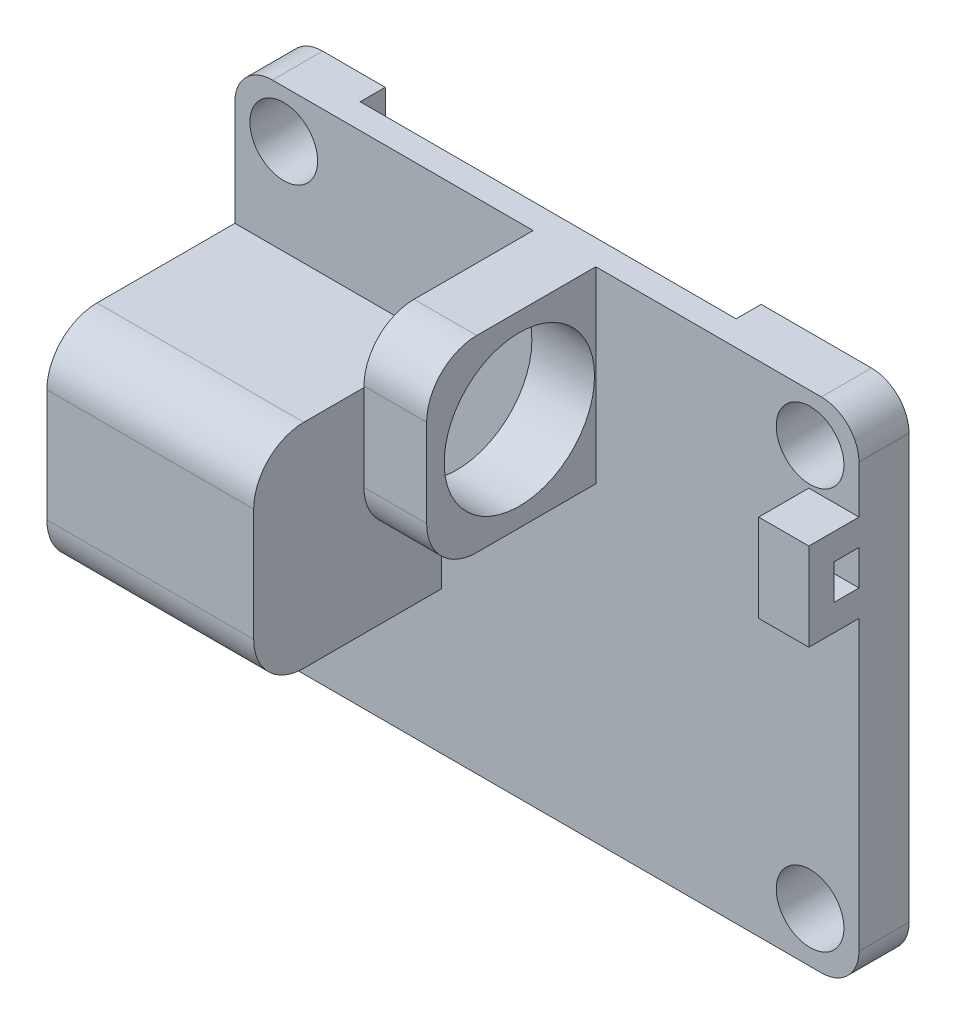
SolidWorks part; units mm, degrees
ref_plane "Alzado" through (0, 0, 0) normal (0, 0, 1) x (1, 0, 0)
ref_plane "Planta" through (0, 0, 0) normal (0, 1, 0) x (1, 0, 0)
ref_plane "Vista lateral" through (0, 0, 0) normal (1, 0, 0) x (0, 0, -1)
sketch "Croquis1" plane through (0, 0, 0) normal (0, 0, 1) x (1, 0, 0)
  line L1 (-56.8634, 16.1421) -> (-7.0634, 16.1421)
  line L2 (-56.8634, 16.1421) -> (-56.8634, -23.6579)
  line L3 (-56.8634, -23.6579) -> (-7.0634, -23.6579)
  line L4 (-7.0634, 16.1421) -> (-7.0634, -23.6579)
  circle A0 centre (-52.9634, 12.3421) radius 2.7
  circle A1 centre (-10.9634, 12.3421) radius 2.7
  circle A2 centre (-10.9634, -19.6579) radius 2.7
  circle A3 centre (-52.9634, -19.6579) radius 2.7
  dimension "D3" = 3.8
  dimension "D7" = 5.4
  dimension "D1" = 49.8
  dimension "D2" = 39.8
  dimension "D4" = 3.9
  dimension "D5" = 2
  dimension "D6" = 2
extrude "Saliente-Extruir1" add sketch "Croquis1" along normal blind 6
sketch "Croquis2" plane through (0, 0, 6) normal (0, 0, 1) x (1, 0, 0)
  line L0 (-56.8634, -23.6579) -> (-7.0634, 16.1421) construction
  line L2 (-49.9634, -16.7579) -> (-13.9634, -16.7579)
  line L3 (-51.9634, -14.7579) -> (-51.9634, 7.2421)
  line L4 (-49.9634, 9.2421) -> (-13.9634, 9.2421)
  line L5 (-11.9634, -14.7579) -> (-11.9634, 7.2421)
  line L6 (-51.9634, -16.7579) -> (-11.9634, 9.2421) construction
  line L7 (-51.9634, 9.2421) -> (-11.9634, -16.7579) construction
  arc A0 (-11.9634, 7.2421) -> (-13.9634, 9.2421) centre (-13.9634, 7.2421) ccw
  arc A1 (-11.9634, -14.7579) -> (-13.9634, -16.7579) centre (-13.9634, -14.7579) cw
  arc A2 (-49.9634, -16.7579) -> (-51.9634, -14.7579) centre (-49.9634, -14.7579) cw
  arc A3 (-49.9634, 9.2421) -> (-51.9634, 7.2421) centre (-49.9634, 7.2421) ccw
  point P4 (-31.9634, -3.7579)
  dimension "D3" = 2
  dimension "D1" = 40
  dimension "D2" = 26
extrude "Cortar-Extruir1" cut sketch "Croquis2" against normal blind 4
sketch "Croquis4" plane through (0, 0, 0) normal (0, 0, -1) x (-1, 0, 0)
  line L1 (56.8634, 16.1421) -> (56.8634, -23.6579) construction
  line L2 (56.8634, 4.2421) -> (61.8634, 4.2421)
  line L4 (61.8634, -11.7579) -> (56.8634, -11.7579)
  line L6 (56.8634, 4.2421) -> (61.8634, -11.7579) construction
  line L7 (57.8634, -0.2579) -> (61.8634, -0.2579)
  line L8 (57.8634, -7.2579) -> (61.8634, -7.2579)
  line L9 (61.8634, 4.2421) -> (61.8634, -0.2579)
  line L10 (61.8634, -7.2579) -> (61.8634, -11.7579)
  line L11 (56.8634, 4.2421) -> (56.8634, -0.4038)
  line L12 (56.8634, -7.112) -> (56.8634, -11.7579)
  arc A2 (57.8634, -0.2579) -> (56.8634, -0.4038) centre (57.8634, -3.7579) ccw
  arc A3 (57.8634, -7.2579) -> (56.8634, -7.112) centre (57.8634, -3.7579) cw
  dimension "D1" = 5
  dimension "D2" = 3.5
  dimension "D3" = 5
extrude "Saliente-Extruir3" add sketch "Croquis4" against normal blind 3
sketch "Croquis5" plane through (0, 0, 3) normal (0, 0, 1) x (1, 0, 0)
  circle A1 centre (-57.8634, -3.7579) radius 6.35
extrude "Cortar-Extruir2" cut sketch "Croquis5" along normal up to vertex (3 mm away)
sketch "Croquis6" plane through (0, 0, 3) normal (0, 0, 1) x (1, 0, 0)
  line L6 (-61.8634, 4.2421) -> (-51.9634, 4.2421)
  line L8 (-51.9634, -11.7579) -> (-61.8634, -11.7579)
  line L9 (-61.8634, 4.2421) -> (-61.8634, 1.1739)
  line L10 (-61.8634, -0.2579) -> (-61.8634, 4.2421) construction
  line L11 (-61.8634, -11.7579) -> (-61.8634, -8.6897)
  line L12 (-51.9634, 4.2421) -> (-48.9634, 4.2421)
  line L13 (-48.9634, 4.2421) -> (-48.9634, -11.7579)
  line L14 (-48.9634, -11.7579) -> (-51.9634, -11.7579)
  arc A5 (-61.8634, 1.1739) -> (-61.8634, -8.6897) centre (-57.8634, -3.7579) cw
extrude "Saliente-Extruir4" add sketch "Croquis6" along normal blind 10
sketch "Croquis7" plane through (0, 0, 2) normal (0, 0, 1) x (1, 0, 0)
  line L0 (-51.9634, -3.7579) -> (-51.9634, 4.2421)
  line L1 (-51.9634, 7.2421) -> (-51.9634, -14.7579) construction
  line L2 (-51.9634, 4.2421) -> (-48.9634, 4.2421)
  line L3 (-48.9634, 4.2421) -> (-48.9634, -11.7579)
  line L4 (-48.9634, -11.7579) -> (-51.9634, -11.7579)
  line L5 (-51.9634, -11.7579) -> (-51.9634, -3.7579)
extrude "Saliente-Extruir5" add sketch "Croquis7" along normal blind 2
sketch "Croquis8" plane through (0, 0, 3) normal (0, 0, 1) x (1, 0, 0)
  line L0 (-56.8634, -0.4038) -> (-56.8634, -7.112)
  arc A0 (-56.8634, -0.4038) -> (-56.8634, -7.112) centre (-56.8634, -3.7579) cw
extrude "Cortar-Extruir3" cut sketch "Croquis8" against normal up to vertex
sketch "Croquis9" plane through (0, 0, 6) normal (0, 0, 1) x (1, 0, 0)
  line L0 (-56.8634, -11.7579) -> (-56.8634, -27.4922)
  line L1 (-56.8634, -27.4922) -> (-1.8171, -27.4922)
  line L2 (-1.8171, -27.4922) -> (-1.8171, 22.8618)
  line L3 (-1.8171, 22.8618) -> (-56.8634, 22.8618)
  line L4 (-56.8634, 22.8618) -> (-56.8634, 4.2421)
  line L5 (-56.8634, 4.2421) -> (-47.1727, 4.2421)
  line L6 (-47.1727, 4.2421) -> (-47.1727, -11.7579)
  line L7 (-47.1727, -11.7579) -> (-56.8634, -11.7579)
extrude "Cortar-Extruir4" cut sketch "Croquis9" against normal blind 4
sketch "Croquis10" plane through (0, 0, 2) normal (0, 0, 1) x (1, 0, 0)
  line L0 (-7.0634, -23.6579) -> (-7.0634, 16.1421) construction
  line L1 (-7.0634, 9.3421) -> (-11.0634, 9.3421)
  line L2 (-7.0634, 9.3421) -> (-7.0634, 2.3421)
  line L3 (-7.0634, 2.3421) -> (-11.0634, 2.3421)
  line L4 (-11.0634, 9.3421) -> (-11.0634, 2.3421)
  circle A0 centre (-10.9634, 12.3421) radius 2.7 construction
  point P6 (-9.0634, 9.3421)
  dimension "D1" = 7
  dimension "D2" = 3
  dimension "D3" = 4
extrude "Saliente-Extruir6" add sketch "Croquis10" along normal blind 4
sketch "Croquis11" plane through (-7.0634, 0, 0) normal (1, 0, 0) x (0, 0, -1)
  line L0 (-6, 5.8421) -> (-2, 5.8421) construction
  line L1 (-6, 2.3421) -> (-6, 9.3421) construction
  line L2 (-2, 5.8421) -> (-2, 7.2421)
  line L3 (-2, 7.2421) -> (-4, 7.2421)
  line L4 (-4, 7.2421) -> (-4, 4.4421)
  line L5 (-4, 4.4421) -> (-2, 4.4421)
  line L6 (-2, 4.4421) -> (-2, 5.8421)
  dimension "D1" = 1.4
  dimension "D2" = 1.4
extrude "Cortar-Extruir5" cut sketch "Croquis11" against normal up to vertex
ref_plane "Plano2" through (-48.9634, 4.2421, 13) normal (0, 1, 0) x (1, 0, 0)
sketch "Croquis16" plane through (0, 0, 2) normal (0, 0, 1) x (1, 0, 0)
  line L1 (-64.1981, 16.945) -> (-35.2393, 16.945)
  line L2 (-64.1981, 16.945) -> (-64.1981, -30.9257)
  line L3 (-64.1981, -30.9257) -> (-35.2393, -30.9257)
  line L4 (-35.2393, 16.945) -> (-35.2393, -30.9257)
extrude "Cortar-Extruir6" cut sketch "Croquis16" along normal up to vertex (2 mm away)
sketch "Croquis17" plane through (0, 0, 2) normal (0, 0, 1) x (1, 0, 0)
  line L1 (-61.8634, 4.2421) -> (-56.8634, 4.2421)
  line L2 (-61.8634, 4.2421) -> (-61.8634, -11.7579)
  line L3 (-61.8634, -11.7579) -> (-56.8634, -11.7579)
  line L4 (-56.8634, 4.2421) -> (-56.8634, -11.7579)
extrude "Cortar-Extruir7" cut sketch "Croquis17" against normal blind 10
sketch "Croquis18" plane through (0, 0, 2) normal (0, 0, 1) x (1, 0, 0)
  line L0 (-56.8634, -0.4038) -> (-50.5134, -0.4038)
  line L1 (-56.8634, -7.112) -> (-50.5134, -7.112)
  line L2 (-56.8634, -0.4038) -> (-56.8634, -7.112)
  arc A0 (-50.5134, -0.4038) -> (-50.5134, -7.112) centre (-50.5134, -3.7579) cw
extrude "Cortar-Extruir8" cut sketch "Croquis18" against normal up to vertex (2 mm away)
sketch "Croquis19" plane through (0, 0, 2) normal (0, 0, 1) x (1, 0, 0)
  line L0 (-55.9053, -0.4038) -> (-56.8634, -0.4038)
  line L1 (-50.5134, -0.4038) -> (-56.8634, -0.4038) construction
  line L2 (-56.8634, -0.4038) -> (-56.8634, 2.5962)
  line L3 (-56.8634, 16.1421) -> (-56.8634, -0.4038) construction
  line L4 (-55.9053, -7.112) -> (-56.8634, -7.112)
  line L5 (-56.8634, -7.112) -> (-50.5134, -7.112) construction
  line L6 (-56.8634, -7.112) -> (-56.8634, -10.112)
  line L7 (-56.8634, -7.112) -> (-56.8634, -23.6579) construction
  circle A0 centre (-50.5134, -3.7579) radius 6.35
  arc A1 (-56.8634, 2.5962) -> (-56.8634, -10.112) centre (-50.5093, -3.7579) cw
  dimension "D1" = 3
sketch "Croquis20" plane through (0, 0, 2) normal (0, 0, 1) x (1, 0, 0)
  line L0 (-56.8634, -0.4038) -> (-56.8634, -7.112)
  line L1 (-56.8634, -7.112) -> (-50.5134, -7.112)
  line L2 (-56.8634, -0.4038) -> (-50.5134, -0.4038)
  arc A0 (-50.5134, -0.4038) -> (-50.5134, -7.112) centre (-50.5134, -3.7579) cw
extrude "Saliente-Extruir7" add sketch "Croquis20" against normal up to vertex (2 mm away)
sketch "Croquis22" plane through (-56.8634, 0, 0) normal (-1, 0, 0) x (0, 0, 1)
  line L0 (2, -3.7579) -> (2, 4.7421)
  line L1 (2, 16.1421) -> (2, -23.6579) construction
  line L2 (2, 4.7421) -> (13, 4.7421)
  line L3 (17, 0.7421) -> (17, -8.2579)
  line L4 (13, -12.2579) -> (2, -12.2579)
  line L5 (2, -12.2579) -> (2, -3.7579)
  line L6 (2, -3.7579) -> (8.55, -3.7579) construction
  arc A1 (17, -8.2579) -> (13, -12.2579) centre (13, -8.2579) cw
  arc A2 (13, 4.7421) -> (17, 0.7421) centre (13, 0.7421) cw
  circle A3 centre (8.55, -3.7579) radius 6.5
  dimension "D1" = 4
  dimension "D2" = 6.55
extrude "Saliente-Extruir9" add sketch "Croquis22" against normal blind 15
sketch "Croquis23" plane through (-41.8634, 0, 0) normal (1, 0, 0) x (0, 0, -1)
  line L0 (-13, -12.2579) -> (-2, -12.2579)
  line L1 (-2, -12.2579) -> (-2, 4.7421)
  line L2 (-2, 4.7421) -> (-13, 4.7421)
  line L3 (-17, 0.7421) -> (-17, -8.2579)
  arc A0 (-13, -12.2579) -> (-17, -8.2579) centre (-13, -8.2579) cw
  arc A1 (-17, 0.7421) -> (-13, 4.7421) centre (-13, 0.7421) cw
extrude "Saliente-Extruir10" add sketch "Croquis23" along normal blind 1.5
sketch "Croquis25" plane through (0, 0, 2) normal (0, 0, 1) x (1, 0, 0)
  line L1 (-33.0634, 16.1421) -> (-28.0634, 16.1421)
  line L2 (-33.0634, 16.1421) -> (-33.0634, 1.1421)
  line L3 (-33.0634, 1.1421) -> (-28.0634, 1.1421)
  line L4 (-28.0634, 16.1421) -> (-28.0634, 1.1421)
  line L6 (-7.0634, -23.6579) -> (-7.0634, 2.3421) construction
  dimension "D1" = 15
  dimension "D2" = 5
  dimension "D3" = 21
extrude "Saliente-Extruir11" add sketch "Croquis25" along normal blind 13.5
sketch "Croquis26" plane through (-28.0634, 0, 0) normal (1, 0, 0) x (0, 0, -1)
  line L0 (-2, 8.6421) -> (-8.1, 8.6421) construction
  line L1 (-2, 1.1421) -> (-2, 16.1421) construction
  circle A0 centre (-8.1, 8.6421) radius 6
extrude "Cortar-Extruir9" cut sketch "Croquis26" against normal up to vertex
fillet "Redondeo2" radius 4 2 edges at (-30.5634, 1.1421, 15.5) (-30.5634, 16.1421, 15.5)
sketch "Croquis27" plane through (0, 0, 0) normal (0, 0, -1) x (-1, 0, 0)
  line L0 (7.0634, 16.1421) -> (56.8634, 16.1421) construction
  line L1 (56.8634, -23.6579) -> (48.8634, -23.6579)
  line L2 (56.8634, -23.6579) -> (56.8634, 16.1421)
  line L3 (56.8634, 16.1421) -> (48.8634, 16.1421)
  line L4 (48.8634, -23.6579) -> (48.8634, 16.1421)
  line L6 (7.0634, -23.6579) -> (18.8634, -23.6579)
  line L7 (7.0634, -23.6579) -> (7.0634, 16.1421)
  line L8 (7.0634, 16.1421) -> (18.8634, 16.1421)
  line L9 (18.8634, -23.6579) -> (18.8634, 16.1421)
  circle A0 centre (52.9634, -19.6579) radius 2.7
  circle A1 centre (52.9634, 12.3421) radius 2.7
  circle A2 centre (10.9634, 12.3421) radius 2.7
  circle A3 centre (10.9634, -19.6579) radius 2.7
  dimension "D1" = 8
  dimension "D2" = 30
extrude "Saliente-Extruir13" add sketch "Croquis27" along normal blind 2
fillet "Redondeo3" radius 3 4 edges at (-7.0634, 16.1421, 0) (-7.0634, -23.6579, 0) (-56.8634, 16.1421, 0) (-56.8634, -23.6579, 0)
